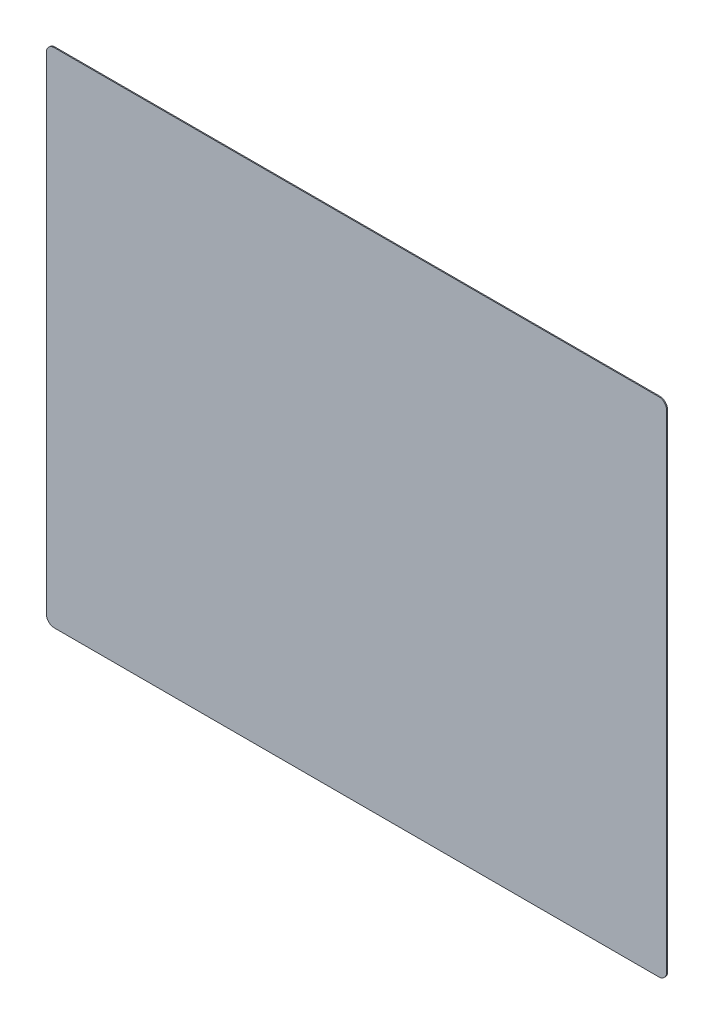
SolidWorks part; units mm, degrees
material "PC High Viscosity"
ref_plane "Front Plane" through (0, 0, 0) normal (0, 0, 1) x (1, 0, 0)
ref_plane "Top Plane" through (0, 0, 0) normal (0, 1, 0) x (1, 0, 0)
ref_plane "Right Plane" through (0, 0, 0) normal (1, 0, 0) x (0, 0, -1)
sketch "Sketch1" plane through (0, 0, 0) normal (0, 0, 1) x (1, 0, 0)
  line L1 (-501.65, 406.4) -> (501.65, 406.4)
  line L2 (-501.65, 406.4) -> (-501.65, -406.4)
  line L3 (-501.65, -406.4) -> (501.65, -406.4)
  line L4 (501.65, 406.4) -> (501.65, -406.4)
  line L5 (-501.65, 406.4) -> (501.65, -406.4) construction
  line L6 (-501.65, -406.4) -> (501.65, 406.4) construction
  point P0 (0, 0)
  dimension "D1" = 1003.3
  dimension "D2" = 812.8
extrude "Boss-Extrude1" add sketch "Sketch1" along normal blind 1.5875
fillet "Fillet1" radius 12.7 4 edges at (501.65, -406.4, 0.7937) (501.65, 406.4, 0.7937) (-501.65, -406.4, 0.7937) (-501.65, 406.4, 0.7937)
